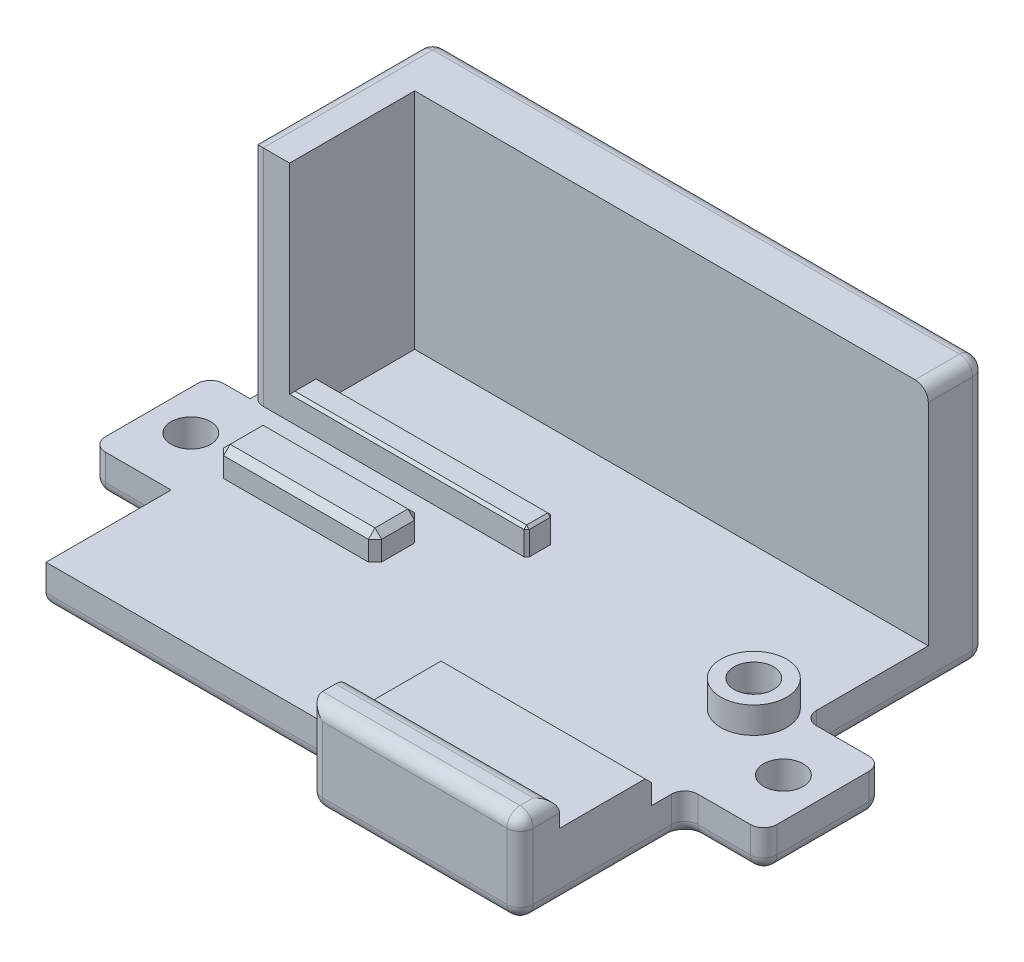
SolidWorks part; units mm, degrees
ref_plane "Plan de face" through (0, 0, 0) normal (0, 0, 1) x (1, 0, 0)
ref_plane "Plan de dessus" through (0, 0, 0) normal (0, 1, 0) x (1, 0, 0)
ref_plane "Plan de droite" through (0, 0, 0) normal (1, 0, 0) x (0, 0, -1)
sketch "Esquisse1" plane through (0, 0, 0) normal (0, 1, 0) x (1, 0, 0)
  line L0 (-19.5, 4.5) -> (-25.5, 4.5)
  line L1 (-19.5, 14) -> (19.5, 14)
  line L2 (-19.5, 14) -> (-19.5, -14)
  line L3 (-19.5, -14) -> (19.5, -14)
  line L4 (19.5, 14) -> (19.5, -14)
  line L5 (-25.5, 4.5) -> (-25.5, -4.5)
  line L6 (-25.5, -4.5) -> (-19.5, -4.5)
  line L7 (-34.3228, 0) -> (34.6777, 0) construction
  line L10 (0, 15.8219) -> (0, -25.5549) construction
  line L11 (19.5, 4.5) -> (25.5, 4.5)
  line L12 (25.5, -4.5) -> (19.5, -4.5)
  line L13 (25.5, 4.5) -> (25.5, -4.5)
  circle A0 centre (17, 3.25) radius 1.55
  circle A1 centre (-22.5, 0) radius 1.5
  circle A2 centre (22.5, 0) radius 1.5
  point P33 (0, 0)
  dimension "D3" = 3.1
  dimension "D4" = 10.75
  dimension "D5" = 2.5
  dimension "D10" = 3
  dimension "D11" = 3
  dimension "D1" = 39
  dimension "D2" = 28
  dimension "D6" = 6
  dimension "D7" = 9
  dimension "D8" = 4.5
  dimension "D9" = 14
extrude "Boss.-Extru.2" add sketch "Esquisse1" along normal blind 3 contours L5 L6 L2 L0 A1 | L4 L1 L2 L3 A0 | L13 L11 L4 L12 A2
sketch "Esquisse2" plane through (0, 3, 0) normal (0, 1, 0) x (1, 0, 0)
  line L0 (11.2912, 0) -> (-29.9229, 0) construction
  line L1 (-18.7652, 1.75) -> (-6.7652, 1.75)
  line L2 (-18.7652, 1.75) -> (-18.7652, -1.75)
  line L3 (-18.7652, -1.75) -> (-6.7652, -1.75)
  line L4 (-6.7652, 1.75) -> (-6.7652, -1.75)
  dimension "D1" = 3.5
  dimension "D2" = 1.75
  dimension "D3" = 12
extrude "Boss.-Extru.3" add sketch "Esquisse2" along normal blind 2
sketch "Esquisse5" plane through (0, 0, 0) normal (0, -1, 0) x (1, 0, 0)
  line L1 (-1.5, -6.5) -> (-19.5, -6.5)
  line L2 (-1.5, -6.5) -> (-1.5, -4.5)
  line L3 (-1.5, -4.5) -> (-19.5, -4.5)
  line L4 (-19.5, -6.5) -> (-19.5, -4.5)
  line L5 (-19.5, -14) -> (-19.5, -4.5) construction
  point P4 (0, 0)
  point P5 (-19.5, -4.5)
  point P6 (-19.5, -6.5)
  dimension "D1" = 2
  dimension "D3" = 18
chamfer "Chanfrein1" distance 0.5 angle 45 8 edges at (-18.7652, 4, 1.75) (-6.7652, 5, 0) (-6.7652, 4, 1.75) (-12.7652, 5, 1.75) (-18.7652, 5, 0) (-18.7652, 4, -1.75) (-12.7652, 5, -1.75) (-6.7652, 4, -1.75)
sketch "Esquisse7" plane through (0, 3, 0) normal (0, 1, 0) x (1, 0, 0)
  circle A0 centre (17, 3.25) radius 1.5
  circle A1 centre (17, 3.25) radius 2.5
  dimension "D1" = 5
extrude "Boss.-Extru.6" add sketch "Esquisse7" along normal blind 2
extrude "Boss.-Extru.7" add sketch "Esquisse5" against normal blind 5
chamfer "Chanfrein2" distance 0.2 angle 45 6 edges at (-1.5, 4, -6.5) (-1.5, 4, -4.5) (-19.5, 5, -5.5) (-10.5, 5, -4.5) (-1.5, 5, -5.5) (-10.5, 5, -6.5)
sketch "Esquisse8" plane through (0, 3, 0) normal (0, 1, 0) x (1, 0, 0)
  line L1 (19.5, -14) -> (3.5, -14)
  line L2 (19.5, -14) -> (19.5, -7)
  line L3 (19.5, -7) -> (3.5, -7)
  line L4 (3.5, -14) -> (3.5, -7)
  dimension "D1" = 7
  dimension "D2" = 16
extrude "Boss.-Extru.8" add sketch "Esquisse8" along normal blind 2
chamfer "Chanfrein3" distance 0.5 angle 45 3 edges at (11.5, 5, 7) (3.5, 4, 7) (3.5, 5, 10.5)
sketch "Esquisse9" plane through (0, 0, 0) normal (0, -1, 0) x (1, 0, 0)
  line L4 (-19.5, -14) -> (19.5, -14)
  line L7 (-22.5, -4.5) -> (-22.5, -18.3648)
  line L8 (-19.5, -4.5) -> (-25.5, -4.5) construction
  line L9 (-22.5, -18.3648) -> (19.5, -18.3648)
  line L10 (19.5, -18.3648) -> (19.5, -14)
  line L11 (-22.5, -4.5) -> (-19.5, -4.5)
  line L12 (-19.5, -4.5) -> (-19.5, -14)
extrude "Boss.-Extru.9" add sketch "Esquisse9" against normal blind 20
sketch "Esquisse11" plane through (0, 0, 0) normal (0, -1, 0) x (1, 0, 0)
  line L0 (19.5, 14) -> (3.5, 14)
  line L1 (-19.5, 14) -> (19.5, 14) construction
  line L2 (3.5, 14) -> (3.5, 17)
  line L3 (3.5, 17) -> (19.5, 17)
  line L4 (19.5, 17) -> (19.5, 14)
  dimension "D1" = 16
  dimension "D2" = 3
extrude "Boss.-Extru.10" add sketch "Esquisse11" against normal blind 7
fillet "Congé1" radius 1 30 edges at (-24, 0, -4.5) (19.5, 20, -16.1824) (-1.5, 20, -18.3648) (19.5, 10, -18.3648) (-22.5, 20, -11.4324) (-22.5, 10, -18.3648) (-22.5, 0, -11.4324) (-1.5, 0, -18.3648) (19.5, 0, -11.4324) (22.5, 0, -4.5) (11.5, 7, 14) (25.5, 0, 0) (19.5, 7, 15.5) (19.5, 3.5, 17) (11.5, 7, 17) (3.5, 3.5, 17) (11.5, 0, 17) (3.5, 0, 15.5) (22.5, 0, 4.5) (19.5, 0, 10.75) (-8, 0, 14) (-19.5, 0, 9.25) (-22.5, 0, 4.5) (-25.5, 0, 0) (-25.5, 1.5, -4.5) (19.5, 1.5, -4.5) (25.5, 1.5, -4.5) (25.5, 1.5, 4.5) (19.5, 1.5, 4.5) (-25.5, 1.5, 4.5)
